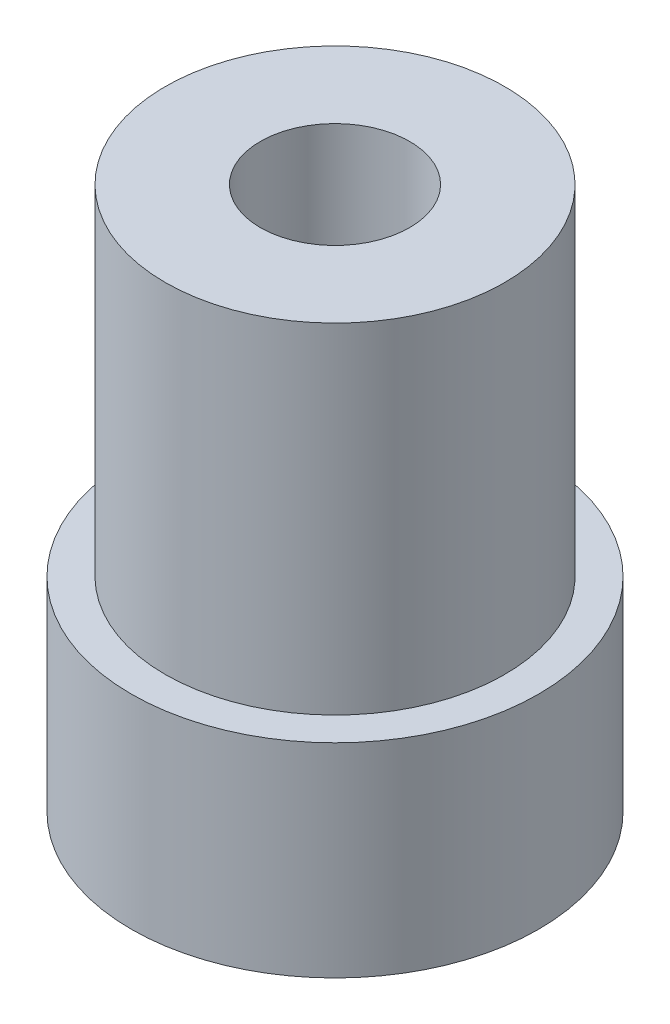
SolidWorks part; units mm, degrees
ref_plane "前基準面" through (0, 0, 0) normal (0, 0, 1) x (1, 0, 0)
ref_plane "上基準面" through (0, 0, 0) normal (0, 1, 0) x (1, 0, 0)
ref_plane "右基準面" through (0, 0, 0) normal (1, 0, 0) x (0, 0, -1)
sketch "草圖1" plane through (0, 0, 0) normal (1, 0, 0) x (0, 0, -1)
  line L0 (0, 0) -> (3, 0)
  line L1 (3, 0) -> (3, 3)
  line L2 (3, 3) -> (2.5, 3)
  line L3 (2.5, 3) -> (2.5, 8)
  line L4 (2.5, 8) -> (0, 8)
  line L5 (0, 8) -> (0, 0)
  dimension "D1" = 2.5
  dimension "D2" = 3
  dimension "D3" = 3
  dimension "D4" = 8
revolve "旋轉1" add sketch "草圖1" angle 360 about L5
hole_wizard "Ø1.0mm 定位孔1" positions "草圖5" profile "草圖3" hole size "Ø1.0" standard "ISO" end condition through all
sketch "草圖5" plane through (0, 8, 0) normal (0, 1, 0) x (1, 0, 0)
  point P0 (0, 0)
sketch "草圖3" plane through (0, 8, 0) normal (1, 0, 0) x (0, 0, 1)
  line L0 (0, 0) -> (0, 8)
  line L1 (0, 8) -> (1.1, 8)
  line L2 (1.1, 8) -> (1.1, 0)
  line L5 (1.1, 0) -> (0, 0)
  line L11 (0, -6.35) -> (0, 107.95) construction
  dimension "貫穿孔直徑" = 2.2
  dimension "貫穿孔深度" = 8
